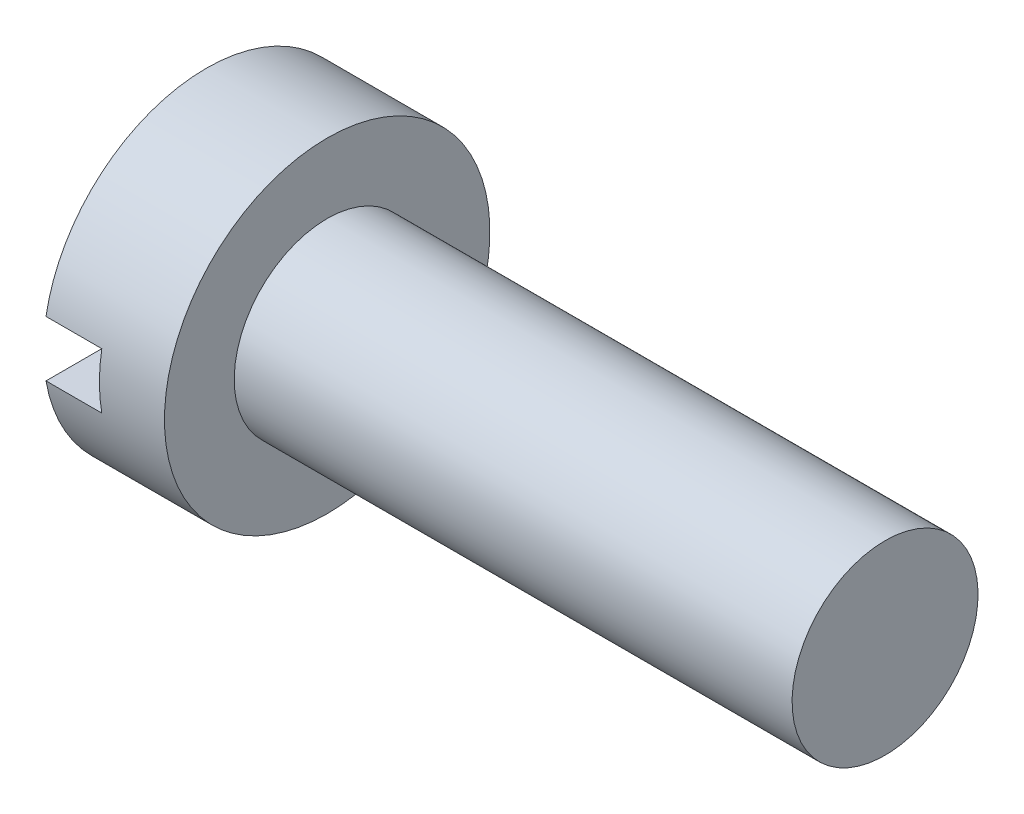
SolidWorks part; units mm, degrees
material "Plain Carbon Steel"
ref_plane "Front Plane" through (0, 0, 0) normal (0, 0, 1) x (1, 0, 0)
ref_plane "Top Plane" through (0, 0, 0) normal (0, 1, 0) x (1, 0, 0)
ref_plane "Right Plane" through (0, 0, 0) normal (1, 0, 0) x (0, 0, -1)
sketch "Sketch1" plane through (0, 0, 0) normal (0, 0, 1) x (1, 0, 0)
  line L0 (0, 0) -> (0, 3.5)
  line L1 (0, 3.5) -> (2.6, 3.5)
  line L2 (2.6, 3.5) -> (2.6, 2)
  line L3 (2.6, 2) -> (14.6, 2)
  line L4 (14.6, 2) -> (14.6, 0)
  line L5 (14.6, 0) -> (0, 0) construction
  line L6 (0, 0) -> (14.6, 0)
  dimension "D1" = 4
  dimension "D2" = 12
  dimension "D3" = 7
  dimension "D4" = 2.6
revolve "Revolve1" add sketch "Sketch1" angle 360 about L5
sketch "Sketch2" plane through (0, 0, 0) normal (-1, 0, 0) x (0, 0, 1)
  line L0 (3.5, 0) -> (-3.5, 0) construction
  line L1 (-3.5, 0.6) -> (3.5, 0.6)
  line L2 (-3.5, 0.6) -> (-3.5, -0.6)
  line L3 (-3.5, -0.6) -> (3.5, -0.6)
  line L4 (3.5, 0.6) -> (3.5, -0.6)
  circle A0 centre (0, 0) radius 3.5 construction
  dimension "D1" = 1.2
extrude "Cut-Extrude1" cut sketch "Sketch2" against normal blind 1.2
